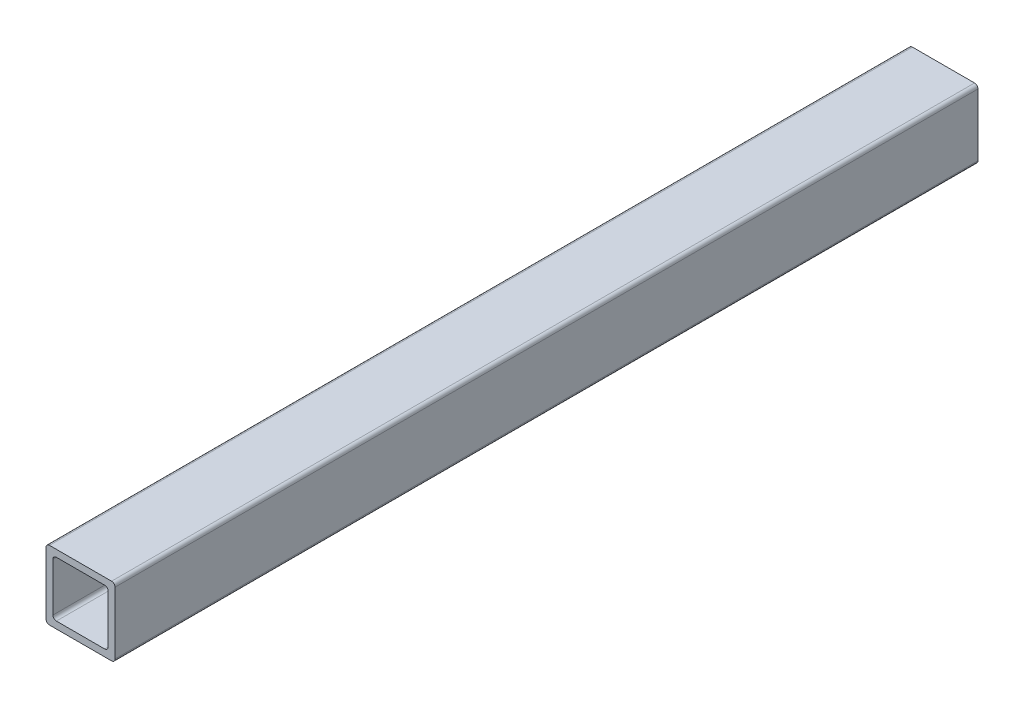
SolidWorks part; units mm, degrees
ref_plane "Plan de face" through (0, 0, 0) normal (0, 0, 1) x (1, 0, 0)
ref_plane "Plan de dessus" through (0, 0, 0) normal (0, 1, 0) x (1, 0, 0)
ref_plane "Plan de droite" through (0, 0, 0) normal (1, 0, 0) x (0, 0, -1)
sketch "Esquisse2" plane through (0, 0, 0) normal (0, 0, 1) x (1, 0, 0)
  line L0 (6, 4) -> (34, 4)
  line L1 (2, 0) -> (38, 0)
  line L2 (0, 2) -> (0, 38)
  line L3 (2, 40) -> (38, 40)
  line L4 (40, 2) -> (40, 38)
  line L5 (36, 6) -> (36, 34)
  line L6 (6, 36) -> (34, 36)
  line L7 (4, 6) -> (4, 34)
  line L8 (4, 4) -> (36, 4) construction
  line L9 (36, 4) -> (36, 36) construction
  line L10 (4, 36) -> (36, 36) construction
  line L11 (4, 4) -> (4, 36) construction
  line L12 (0, 0) -> (40, 0) construction
  line L13 (0, 0) -> (0, 40) construction
  line L14 (0, 40) -> (40, 40) construction
  line L15 (40, 0) -> (40, 40) construction
  arc A0 (34, 4) -> (36, 6) centre (34, 6) ccw
  arc A1 (36, 34) -> (34, 36) centre (34, 34) ccw
  arc A2 (6, 36) -> (4, 34) centre (6, 34) ccw
  arc A3 (4, 6) -> (6, 4) centre (6, 6) ccw
  arc A4 (2, 0) -> (0, 2) centre (2, 2) cw
  arc A5 (0, 38) -> (2, 40) centre (2, 38) cw
  arc A6 (38, 40) -> (40, 38) centre (38, 38) cw
  arc A7 (40, 2) -> (38, 0) centre (38, 2) cw
  point P24 (0, 0)
  dimension "D4" = 2
  dimension "D1" = 40
  dimension "D2" = 40
  dimension "D3" = 4
extrude "Boss.-Extru.1" add sketch "Esquisse2" along normal blind 500
